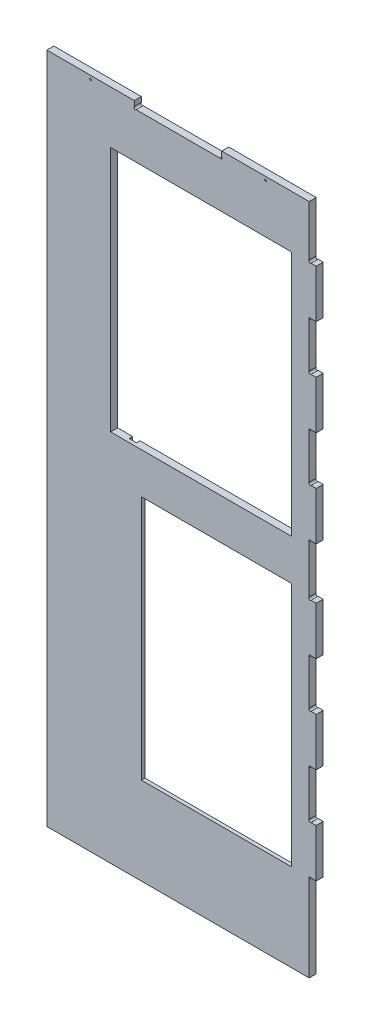
SolidWorks part; units mm, degrees
ref_plane "Plan de face" through (0, 0, 0) normal (0, 0, 1) x (1, 0, 0)
ref_plane "Plan de dessus" through (0, 0, 0) normal (0, 1, 0) x (1, 0, 0)
ref_plane "Plan de droite" through (0, 0, 0) normal (1, 0, 0) x (0, 0, -1)
sketch "Esquisse1" plane through (0, 0, 0) normal (0, 0, 1) x (1, 0, 0)
  line L0 (-54.6501, -45.8192) -> (-54.6501, 358.029)
  line L1 (-54.6501, 722.8961) -> (45.3499, 722.8961)
  line L2 (-54.6501, -45.8192) -> (-46.6501, -45.8192) construction
  line L3 (245.3499, 722.8961) -> (245.3499, 665.0174)
  line L4 (245.3499, -45.8192) -> (-54.6501, -45.8192)
  line L5 (-54.6501, 358.029) -> (245.3499, 358.029) construction
  line L6 (-54.6501, 358.029) -> (-237.0836, 540.4625) construction
  line L7 (-237.0836, 540.4625) -> (-54.6501, 722.8961) construction
  line L8 (-54.6501, 358.029) -> (-54.6501, 722.8961)
  line L9 (18.3499, 662.8961) -> (225.3499, 662.8961)
  line L10 (18.3499, 662.8961) -> (18.3499, 381.3427)
  line L11 (-46.6501, -45.8192) -> (-46.6501, 354.7153) construction
  line L12 (18.3499, 381.3427) -> (225.3499, 381.3427)
  line L13 (-46.6501, 354.7153) -> (203.3499, 604.7153) construction
  line L14 (225.3499, 662.8961) -> (225.3499, 381.3427)
  line L15 (53.3499, 334.7153) -> (225.3499, 334.7153)
  line L16 (53.3499, 334.7153) -> (53.3499, 54.1808)
  line L17 (53.3499, 54.1808) -> (225.3499, 54.1808)
  line L18 (225.3499, 334.7153) -> (225.3499, 54.1808)
  line L19 (-54.6501, 354.7153) -> (245.3499, 354.7153) construction
  line L20 (-54.6501, 358.029) -> (-46.6501, 354.7153) construction
  line L21 (-54.6501, 358.029) -> (-46.6501, 361.3427) construction
  line L22 (-46.6501, 354.7153) -> (-46.6501, 361.3427) construction
  line L23 (-54.6501, 361.3427) -> (245.3499, 361.3427) construction
  line L24 (-54.6501, 662.8961) -> (245.3499, 662.8961) construction
  line L25 (-54.6501, 607.8961) -> (245.3499, 607.8961) construction
  line L26 (-54.6501, 552.8961) -> (245.3499, 552.8961) construction
  line L27 (-54.6501, 497.8961) -> (245.3499, 497.8961) construction
  line L28 (-54.6501, 442.8961) -> (245.3499, 442.8961) construction
  line L29 (-54.6501, 387.8961) -> (245.3499, 387.8961) construction
  line L30 (-54.6501, 54.1808) -> (245.3499, 54.1808) construction
  line L31 (-54.6501, 109.1808) -> (245.3499, 109.1808) construction
  line L32 (-54.6501, 164.1808) -> (245.3499, 164.1808) construction
  line L33 (-54.6501, 219.1808) -> (245.3499, 219.1808) construction
  line L34 (-54.6501, 274.1808) -> (245.3499, 274.1808) construction
  line L35 (-54.6501, 329.1808) -> (245.3499, 329.1808) construction
  line L36 (245.3499, 722.8961) -> (253.3499, 722.8961) construction
  line L37 (253.3499, 722.8961) -> (253.3499, -45.8192) construction
  line L38 (253.3499, -45.8192) -> (245.3499, -45.8192) construction
  line L39 (247.4712, 662.8961) -> (253.3499, 662.8961)
  line L40 (253.3499, 662.8961) -> (253.3499, 607.8961)
  line L41 (253.3499, 607.8961) -> (247.4712, 607.8961)
  line L42 (247.4712, 552.8961) -> (253.3499, 552.8961)
  line L43 (253.3499, 552.8961) -> (253.3499, 497.8961)
  line L44 (253.3499, 497.8961) -> (247.4712, 497.8961)
  line L45 (247.4712, 442.8961) -> (253.3499, 442.8961)
  line L46 (253.3499, 442.8961) -> (253.3499, 387.8961)
  line L47 (253.3499, 387.8961) -> (247.4712, 387.8961)
  line L48 (247.4712, 54.1808) -> (253.3499, 54.1808)
  line L49 (253.3499, 54.1808) -> (253.3499, 109.1808)
  line L50 (253.3499, 109.1808) -> (247.4712, 109.1808)
  line L51 (247.4712, 164.1808) -> (253.3499, 164.1808)
  line L52 (253.3499, 164.1808) -> (253.3499, 219.1808)
  line L53 (253.3499, 219.1808) -> (247.4712, 219.1808)
  line L54 (247.4712, 274.1808) -> (253.3499, 274.1808)
  line L55 (253.3499, 274.1808) -> (253.3499, 329.1808)
  line L56 (253.3499, 329.1808) -> (247.4712, 329.1808)
  line L57 (245.3499, 52.0595) -> (245.3499, -45.8192)
  line L58 (245.3499, 162.0595) -> (245.3499, 111.3021)
  line L59 (245.3499, 272.0595) -> (245.3499, 221.3021)
  line L60 (245.3499, 385.7748) -> (245.3499, 331.3021)
  line L61 (245.3499, 495.7748) -> (245.3499, 445.0174)
  line L62 (245.3499, 605.7748) -> (245.3499, 555.0174)
  line L63 (-54.6501, 749.0762) -> (45.3499, 749.0762) construction
  line L64 (45.3499, 749.0762) -> (145.3499, 749.0762) construction
  line L65 (145.3499, 749.0762) -> (245.3499, 749.0762) construction
  line L66 (45.3499, 722.8961) -> (45.3499, 717.0174)
  line L67 (47.4712, 714.8961) -> (143.2286, 714.8961)
  line L68 (145.3499, 717.0174) -> (145.3499, 722.8961)
  line L69 (145.3499, 722.8961) -> (245.3499, 722.8961)
  line L77 (145.3499, 734.1951) -> (145.3499, 688.6224) construction
  line L78 (245.3499, 734.1951) -> (245.3499, 688.6224) construction
  line L79 (45.3499, 734.1951) -> (45.3499, 688.6224) construction
  line L80 (95.3499, 767.6295) -> (95.3499, 727.5002) construction
  line L81 (195.3499, 734.1951) -> (195.3499, 700.7473) construction
  line L82 (220.241, 718.8961) -> (191.968, 718.8961) construction
  arc A0 (45.3499, 717.0174) -> (47.4712, 714.8961) centre (46.4106, 715.9567) ccw
  arc A1 (143.2286, 714.8961) -> (145.3499, 717.0174) centre (144.2892, 715.9567) ccw
  arc A2 (245.3499, 665.0174) -> (247.4712, 662.8961) centre (246.4106, 663.9567) ccw
  arc A3 (247.4712, 607.8961) -> (245.3499, 605.7748) centre (246.4106, 606.8354) ccw
  arc A4 (245.3499, 555.0174) -> (247.4712, 552.8961) centre (246.4106, 553.9567) ccw
  arc A5 (245.3499, 445.0174) -> (247.4712, 442.8961) centre (246.4106, 443.9567) ccw
  arc A6 (247.4712, 497.8961) -> (245.3499, 495.7748) centre (246.4106, 496.8354) ccw
  arc A7 (247.4712, 387.8961) -> (245.3499, 385.7748) centre (246.4106, 386.8354) ccw
  arc A8 (245.3499, 331.3021) -> (247.4712, 329.1808) centre (246.4106, 330.2415) ccw
  arc A9 (247.4712, 274.1808) -> (245.3499, 272.0595) centre (246.4106, 273.1201) ccw
  arc A10 (245.3499, 221.3021) -> (247.4712, 219.1808) centre (246.4106, 220.2415) ccw
  arc A11 (247.4712, 164.1808) -> (245.3499, 162.0595) centre (246.4106, 163.1201) ccw
  arc A12 (245.3499, 111.3021) -> (247.4712, 109.1808) centre (246.4106, 110.2415) ccw
  arc A13 (247.4712, 54.1808) -> (245.3499, 52.0595) centre (246.4106, 53.1201) ccw
  circle A20 centre (195.3499, 718.8961) radius 1
  circle A21 centre (-4.6501, 718.8961) radius 1
  dimension "D24" = 50
  dimension "D1" = 100
  dimension "D2" = 108
  dimension "D3" = 403.8482
  dimension "D4" = 73
  dimension "D5" = 20
  dimension "D6" = 8
  dimension "D7" = 20
  dimension "D8" = 300
  dimension "D9" = 22.5
  dimension "D10" = 20
  dimension "D11" = 20
  dimension "D12" = 60
  dimension "D13" = 60
  dimension "D14" = 55
  dimension "D15" = 55
  dimension "D16" = 55
  dimension "D17" = 55
  dimension "D18" = 55
  dimension "D19" = 55
  dimension "D20" = 55
  dimension "D21" = 55
  dimension "D22" = 55
  dimension "D23" = 55
  dimension "D25" = 4
  dimension "D26" = 50
extrude "Boss.-Extru.1" add sketch "Esquisse1" along normal blind 8
sketch "Esquisse3" plane through (0, 0, 0) normal (0, 0, -1) x (-1, 0, 0)
  line L0 (-225.3499, 334.7153) -> (-53.3499, 334.7153) construction
  line L1 (-228.2286, 339.7153) -> (-50.4712, 339.7153)
  line L2 (-230.3499, 337.5939) -> (-230.3499, 51.3021)
  line L3 (-228.2286, 49.1808) -> (-50.4712, 49.1808)
  line L4 (-48.3499, 337.5939) -> (-48.3499, 51.3021)
  line L5 (-53.3499, 334.7153) -> (-53.3499, 54.1808) construction
  line L6 (-53.3499, 54.1808) -> (-225.3499, 54.1808) construction
  line L7 (-225.3499, 54.1808) -> (-225.3499, 334.7153) construction
  arc A0 (-228.2286, 339.7153) -> (-230.3499, 337.5939) centre (-229.2892, 338.6546) ccw
  arc A1 (-50.4712, 49.1808) -> (-48.3499, 51.3021) centre (-49.4106, 50.2415) ccw
  arc A2 (-48.3499, 337.5939) -> (-50.4712, 339.7153) centre (-49.4106, 338.6546) ccw
  arc A3 (-230.3499, 51.3021) -> (-228.2286, 49.1808) centre (-229.2892, 50.2415) ccw
  dimension "D1" = 5
  dimension "D2" = 5
  dimension "D3" = 5
  dimension "D4" = 5
extrude "Enlèv. mat.-Extru.2" cut sketch "Esquisse3" against normal blind 4
sketch "Esquisse4" plane through (0, 0, 0) normal (0, 0, -1) x (-1, 0, 0)
  line L1 (76.4743, 358.029) -> (-291.3418, 358.029)
sketch "Esquisse5" plane through (0, 0, 0) normal (0, 0, -1) x (-1, 0, 0)
  line L0 (-35.3499, -45.8192) -> (-43.8499, -45.8192)
  line L1 (-41.8071, 714.9961) -> (-37.3927, 714.9961)
  line L2 (-39.5999, 718.0838) -> (-39.5999, 712.7632) construction
  line L3 (-35.3499, 714.9961) -> (-40.7379, 708.4995) construction
  line L5 (-43.8499, -45.8192) -> (-43.8499, 712.5329)
  line L7 (-35.3499, 722.8962) -> (-35.3499, -45.8192) construction
  line L8 (-35.3499, -45.8192) -> (-43.8499, -45.8192) construction
  line L9 (-35.3499, 712.5329) -> (-35.3499, -45.8192)
  line L10 (54.6501, 722.8961) -> (54.6501, -45.8192) construction
  arc A0 (-35.3499, 712.5329) -> (-37.3927, 714.9961) centre (-36.3713, 713.7645) ccw
  arc A1 (-43.8499, 712.5329) -> (-41.8071, 714.9961) centre (-42.8285, 713.7645) cw
  dimension "D1" = 8.5
  dimension "D2" = 90
  dimension "D3" = 4.25
extrude "Enlèv. mat.-Extru.3" cut sketch "Esquisse5" against normal blind 4
sketch "Esquisse6" plane through (0, 0, 0) normal (0, 0, -1) x (-1, 0, 0)
  line L0 (34.6501, -45.8192) -> (34.6501, -25.8192) construction
  line L1 (54.6501, -45.8192) -> (-35.3499, -45.8192) construction
  line L2 (54.6501, 722.8961) -> (54.6501, -45.8192) construction
  circle A0 centre (34.6501, -25.8192) radius 4
  dimension "D1" = 20
extrude "Enlèv. mat.-Extru.4" cut sketch "Esquisse6" against normal blind 6
